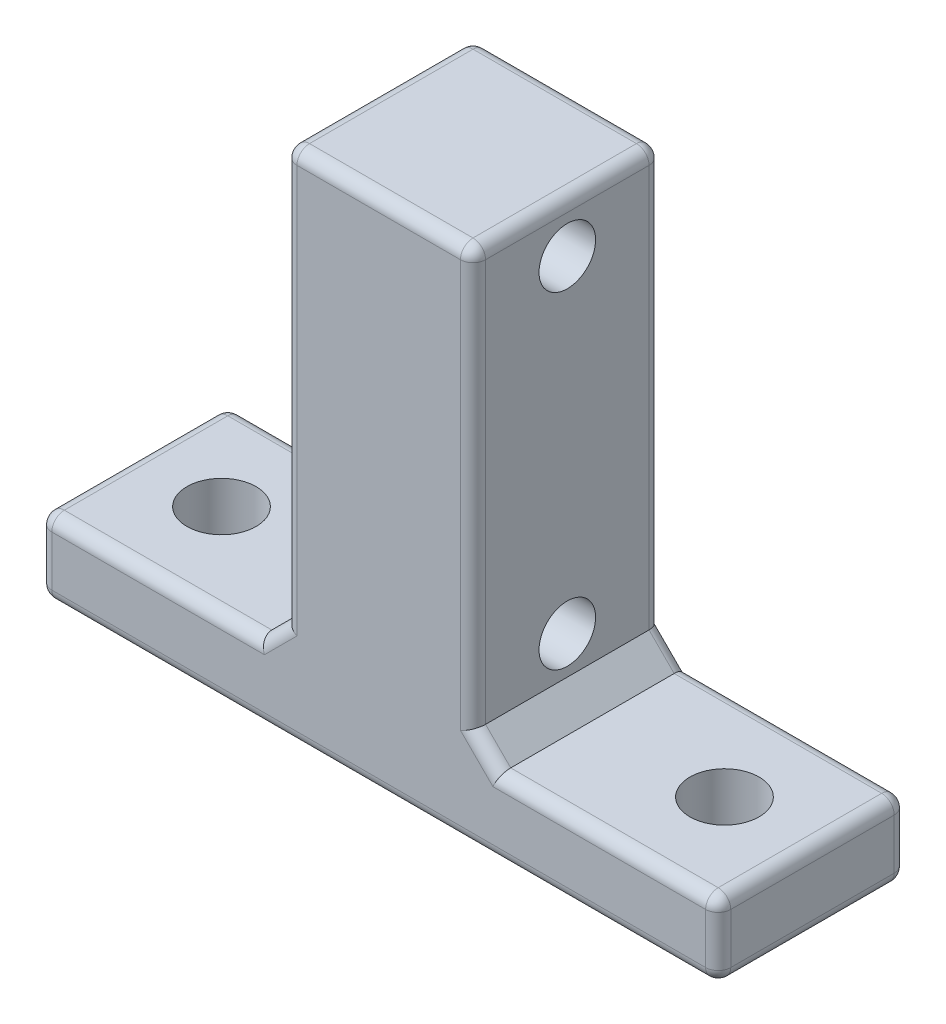
SolidWorks part; units mm, degrees
ref_plane "前视基准面" through (0, 0, 0) normal (0, 0, 1) x (1, 0, 0)
ref_plane "上视基准面" through (0, 0, 0) normal (0, 1, 0) x (1, 0, 0)
ref_plane "右视基准面" through (0, 0, 0) normal (1, 0, 0) x (0, 0, -1)
other "Configuration Table"
sketch "草图1" plane through (0, 0, 0) normal (0, 1, 0) x (1, 0, 0)
  line L0 (-20, 0) -> (20, 0) construction
  line L1 (-27, -7.5) -> (27, -7.5)
  line L2 (-27, -7.5) -> (-27, 7.5)
  line L3 (-27, 7.5) -> (27, 7.5)
  line L4 (27, -7.5) -> (27, 7.5)
  line L5 (-27, -7.5) -> (27, 7.5) construction
  line L6 (-27, 7.5) -> (27, -7.5) construction
  circle A0 centre (-20, 0) radius 2.75
  circle A1 centre (20, 0) radius 2.75
  point P0 (0, 0)
  point P9 (0, 0)
  dimension "D4" = 5.5
  dimension "D1" = 15
  dimension "D2" = 54
  dimension "D3" = 7
extrude "凸台-拉伸1" add sketch "草图1" along normal blind 6
sketch "草图2" plane through (0, 0, 0) normal (0, 0, 1) x (1, 0, 0)
  line L0 (-27, 6) -> (27, 6) construction
  line L1 (-7.5, 41) -> (7.5, 41)
  line L2 (-7.5, 41) -> (-7.5, 6)
  line L3 (-7.5, 6) -> (7.5, 6)
  line L4 (7.5, 41) -> (7.5, 6)
  line L5 (-7.5, 41) -> (7.5, 6) construction
  line L6 (-7.5, 6) -> (7.5, 41) construction
  point P0 (0, 23.5)
  dimension "D1" = 35
  dimension "D2" = 15
extrude "凸台-拉伸2" add sketch "草图2" along normal mid plane 15
sketch "草图3" plane through (-7.5, 0, 0) normal (-1, 0, 0) x (0, 0, 1)
  line L0 (7.5, 6) -> (-7.5, 6) construction
  circle A0 centre (0, 11) radius 2.25
  circle A1 centre (0, 37) radius 2.25
  point P4 (0, 0)
  dimension "D1" = 4.5
  dimension "D2" = 4.5
  dimension "D3" = 5
  dimension "D4" = 26
extrude "切除-拉伸1" cut sketch "草图3" against normal blind 15
chamfer "倒角1" distance 2 angle 45 2 edges at (7.5, 6, 0) (-7.5, 6, 0)
fillet "圆角1" radius 1 26 edges at (7.5, 41, 0) (-7.5, 41, 0) (27, 6, 0) (27, 0, 0) (-27, 6, 0) (-27, 0, 0) (27, 3, -7.5) (18.25, 6, -7.5) (8.5, 7, -7.5) (7.5, 24.5, -7.5) (0, 41, -7.5) (-7.5, 24.5, -7.5) (-8.5, 7, -7.5) (-18.25, 6, -7.5) (-27, 3, -7.5) (0, 0, -7.5) (-27, 3, 7.5) (-18.25, 6, 7.5) (-8.5, 7, 7.5) (-7.5, 24.5, 7.5) (0, 41, 7.5) (7.5, 24.5, 7.5) (8.5, 7, 7.5) (18.25, 6, 7.5) (27, 3, 7.5) (0, 0, 7.5)
